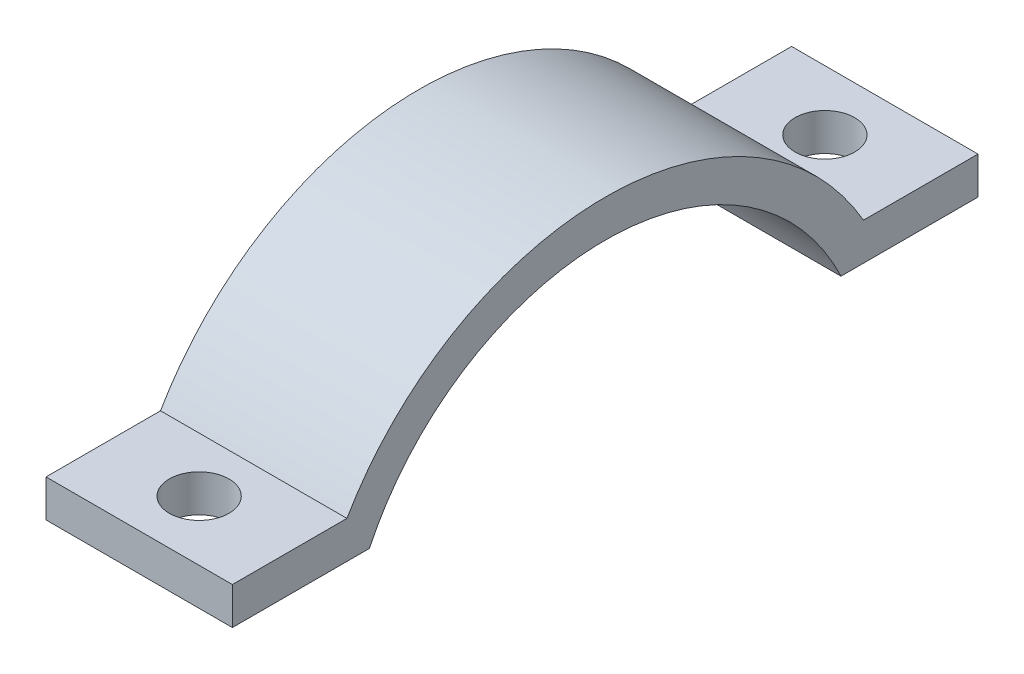
SolidWorks part; units mm, degrees
other "标注1"
sketch "草图5" plane through (0, 15, -20) normal (0, 1, 0) x (0, 0, -1)
ref_plane "前视基准面" through (0, 0, 0) normal (0, 0, 1) x (1, 0, 0)
ref_plane "上视基准面" through (0, 0, 0) normal (0, 1, 0) x (1, 0, 0)
ref_plane "右视基准面" through (0, 0, 0) normal (1, 0, 0) x (0, 0, -1)
other "Configuration Table"
sketch "草图2" plane through (0, 0, 0) normal (1, 0, 0) x (0, 0, -1)
  line L0 (0, 0) -> (50000, 0) construction
  line L1 (-0.4561, 6) -> (49999.5439, 6) construction
  line L2 (-12.6491, 6) -> (-20, 6)
  line L3 (-20, 6) -> (-20, 8)
  line L4 (-20, 8) -> (-13.8564, 8)
  line L5 (12.6491, 6) -> (20, 6)
  line L6 (20, 6) -> (20, 8)
  line L7 (20, 8) -> (13.8564, 8)
  arc A0 (12.6491, 6) -> (-12.6491, 6) centre (0, 0) ccw
  arc A1 (13.8564, 8) -> (-13.8564, 8) centre (0, 0) ccw
  dimension "D1" = 28
  dimension "D2" = 32
  dimension "D3" = 6
  dimension "D4" = 2
  dimension "D5" = 2
  dimension "D6" = 40
extrude "凸台-拉伸1" add sketch "草图2" along normal blind 10
sketch "草图3" plane through (0, 8, 0) normal (0, 1, 0) x (1, 0, 0)
  line L0 (5, -16.785) -> (5, -20) construction
  line L2 (10, -20) -> (0, -20) construction
  line L4 (5, 20) -> (5, 16.785) construction
  line L5 (10, 20) -> (0, 20) construction
  line L6 (5, 16.785) -> (5, -16.785) construction
  circle A0 centre (5, 16.785) radius 1.6
  circle A1 centre (5, -16.785) radius 1.6
  dimension "D1" = 3.2
  dimension "D2" = 33.57
extrude "切除-拉伸1" cut sketch "草图3" against normal blind 10
